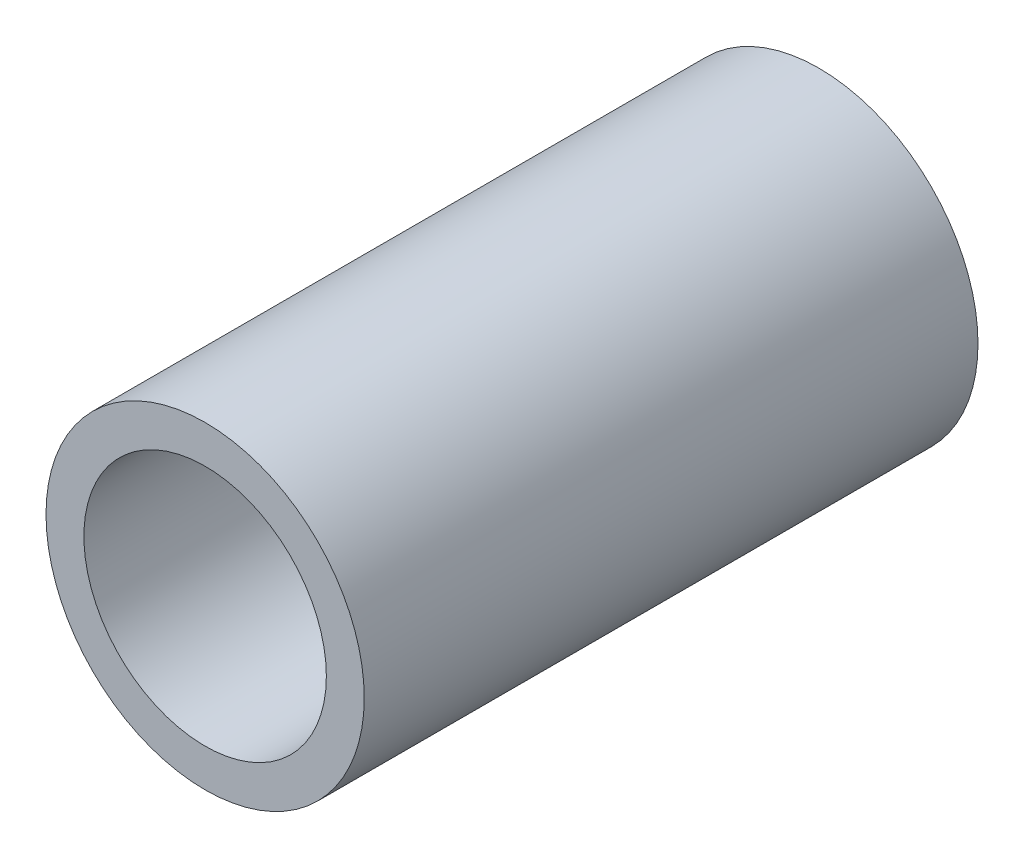
SolidWorks part; units mm, degrees
material "Nickel"
ref_plane "Front Plane" through (0, 0, 0) normal (0, 0, 1) x (1, 0, 0)
ref_plane "Top Plane" through (0, 0, 0) normal (0, 1, 0) x (1, 0, 0)
ref_plane "Right Plane" through (0, 0, 0) normal (1, 0, 0) x (0, 0, -1)
sketch "Sketch1" plane through (0, 0, 0) normal (0, 0, 1) x (1, 0, 0)
  circle A0 centre (0, 0) radius 0.4064
  circle A1 centre (0, 0) radius 0.5334
  dimension "D1" = 1.0668
  dimension "D2" = 0.8128
extrude "Boss-Extrude1" add sketch "Sketch1" along normal blind 2.0574
